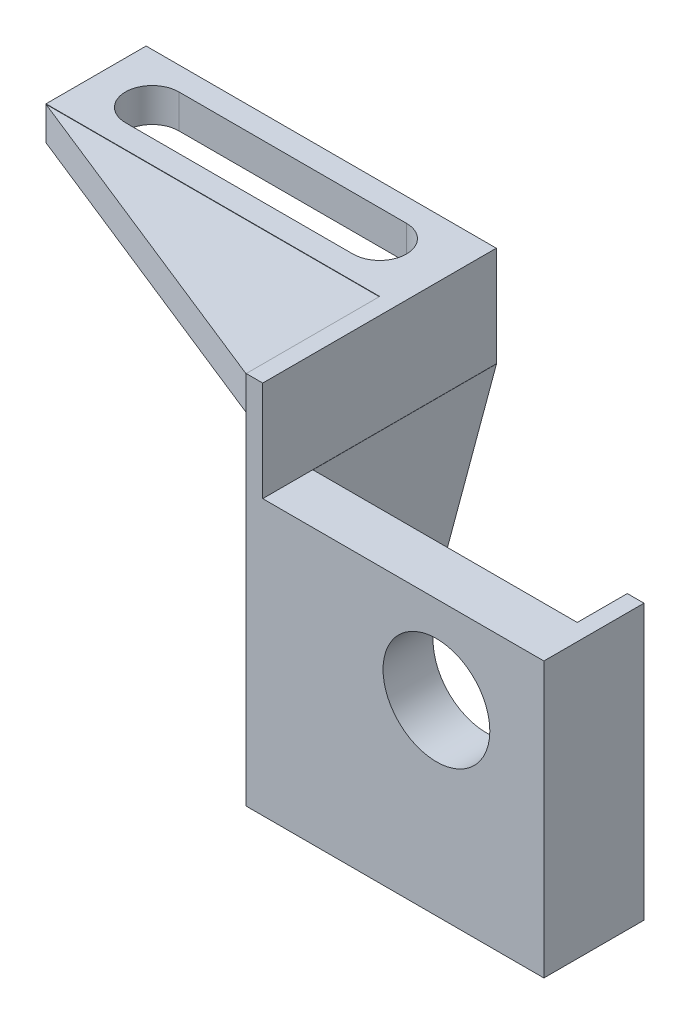
SolidWorks part; units mm, degrees
ref_plane "Front Plane" through (0, 0, 0) normal (0, 0, 1) x (1, 0, 0)
ref_plane "Top Plane" through (0, 0, 0) normal (0, 1, 0) x (1, 0, 0)
ref_plane "Right Plane" through (0, 0, 0) normal (1, 0, 0) x (0, 0, -1)
sketch "Sketch2" plane through (0, 0, 0) normal (0, 0, 1) x (1, 0, 0)
  line L0 (-6.5238, 2.0903) -> (0.8762, 2.0903) construction
  line L1 (-6.5238, 7.3453) -> (6.8762, 7.3453)
  line L2 (-6.5238, 7.3453) -> (-6.5238, -3.1647)
  line L3 (-6.5238, -3.1647) -> (6.8762, -3.1647)
  line L4 (6.8762, 7.3453) -> (6.8762, -3.1647)
  circle A0 centre (0.8762, 2.0903) radius 3.2
  dimension "D4" = 6.4
  dimension "D1" = 13.4
  dimension "D2" = 10.51
  dimension "D3" = 7.4
extrude "Boss-Extrude1" add sketch "Sketch2" along normal blind 3
sketch "Sketch4" plane through (0, 0, 3) normal (0, 0, 1) x (1, 0, 0)
  line L0 (0.8762, -1.1097) -> (0.8762, -9.1097) construction
  line L2 (-6.5238, -3.1647) -> (6.8832, -3.1647)
  line L3 (-6.5238, -3.1647) -> (-6.5238, -9.1097)
  line L4 (-6.5238, -9.1097) -> (6.8832, -9.1097)
  line L5 (6.8832, -3.1647) -> (6.8832, -9.1097)
  circle A0 centre (0.8762, 2.0903) radius 3.2 construction
  dimension "D1" = 8
extrude "Boss-Extrude3" add sketch "Sketch4" against normal blind 3
sketch "Sketch5" plane through (0, 0, 0) normal (0, 0, -1) x (-1, 0, 0)
  line L0 (-0.8762, -1.1097) -> (-0.8762, -6.0797) construction
  circle A0 centre (-0.8762, 2.0903) radius 3.2 construction
  circle A1 centre (-0.8762, -6.0797) radius 1.65
  dimension "D2" = 3.3
  dimension "D1" = 4.97
extrude "Boss-Extrude4" add sketch "Sketch5" along normal blind 3
sketch "Sketch6" plane through (-6.5238, 0, 0) normal (-1, 0, 0) x (0, 0, 1)
  line L0 (0, -7.4091) -> (0, 7.4091) construction
  line L1 (0, 7.3453) -> (3, 7.3453)
  line L2 (0, 7.3453) -> (0, -9.1097)
  line L3 (0, -9.1097) -> (3, -9.1097)
  line L4 (3, 7.3453) -> (3, -9.1097)
  line L5 (3, 7.3453) -> (0, 7.3453) construction
extrude "Boss-Extrude5" add sketch "Sketch6" along normal blind 4
sketch "Sketch7" plane through (0, 0, 0) normal (0, 0, -1) x (-1, 0, 0)
  line L0 (10.5238, -9.1097) -> (-6.8832, -9.1097) construction
  line L1 (10.5238, 7.3453) -> (9.5238, 7.3453)
  line L2 (10.5238, 7.3453) -> (10.5238, -9.1097)
  line L3 (10.5238, -9.1097) -> (9.5238, -9.1097)
  line L4 (9.5238, 7.3453) -> (9.5238, -9.1097)
  dimension "D1" = 1
extrude "Boss-Extrude6" add sketch "Sketch7" along normal blind 5
sketch "Sketch11" plane through (0, 7.3453, 0) normal (0, 1, 0) x (1, 0, 0)
  line L0 (6.8762, -3) -> (-10.5238, -3) construction
  line L1 (-10.5238, 5) -> (-9.5355, 5)
  line L2 (-10.5238, 5) -> (-10.5238, -3)
  line L3 (-10.5238, -3) -> (-9.5355, -3)
  line L4 (-9.5355, 5) -> (-9.5355, -3)
extrude "Boss-Extrude8" add sketch "Sketch11" along normal blind 6
sketch "Sketch16" plane through (0, 0, -5) normal (0, 0, -1) x (-1, 0, 0)
  line L0 (10.5238, -9.1097) -> (10.5238, 13.3453) construction
  line L1 (9.5355, 13.3453) -> (10.5238, 13.3453)
  line L2 (9.5355, 13.3453) -> (9.5355, 7.3453)
  line L3 (9.5355, 7.3453) -> (10.5238, 7.3453)
  line L4 (10.5238, 13.3453) -> (10.5238, 7.3453)
  dimension "D1" = 6
extrude "Boss-Extrude12" add sketch "Sketch16" along normal blind 6
sketch "Sketch17" plane through (-10.5238, 0, 0) normal (-1, 0, 0) x (0, 0, 1)
  line L0 (-11, 7.3453) -> (-5, -9.1097)
  line L1 (-5, -9.1097) -> (-5, 7.3453)
  line L2 (-5, 7.3453) -> (-11, 7.3453)
extrude "Boss-Extrude13" add sketch "Sketch17" against normal blind 1
sketch "Sketch20" plane through (-10.5238, 0, 0) normal (-1, 0, 0) x (0, 0, 1)
  line L1 (-11, 13.3453) -> (-5, 13.3453)
  line L2 (-11, 13.3453) -> (-11, 11.3212)
  line L3 (-11, 11.3212) -> (-5, 11.3212)
  line L4 (-5, 13.3453) -> (-5, 11.3212)
  dimension "D1" = 6
extrude "Boss-Extrude15" add sketch "Sketch20" along normal blind 20
sketch "Sketch21" plane through (0, 11.3212, 0) normal (0, -1, 0) x (1, 0, 0)
  line L0 (-30.5238, -8) -> (-6.5602, -8) construction
  line L1 (-30.5238, -11) -> (-30.5238, -5) construction
  line L2 (-20.5238, -5) -> (-20.5238, -12.6331) construction
  line L3 (-30.5238, -5) -> (-10.5238, -5) construction
  line L4 (-27.1602, -8) -> (-13.5238, -8) construction
  line L5 (-27.1602, -6.4) -> (-13.5238, -6.4)
  line L6 (-27.1602, -9.6) -> (-13.5238, -9.6)
  line L7 (-10.5238, -11) -> (-10.5238, -5) construction
  arc A0 (-27.1602, -6.4) -> (-27.1602, -9.6) centre (-27.1602, -8) ccw
  arc A1 (-13.5238, -9.6) -> (-13.5238, -6.4) centre (-13.5238, -8) ccw
  point P10 (-20.342, -8)
  dimension "D1" = 3.2
  dimension "D2" = 3
extrude "Cut-Extrude3" cut sketch "Sketch21" against normal through all
sketch "Sketch22" plane through (6.8762, 0, 0) normal (1, 0, 0) x (0, 0, -1)
  line L1 (-3, 7.3453) -> (0, 7.3453)
  line L2 (-3, 7.3453) -> (-3, -9.1097)
  line L3 (-3, -9.1097) -> (0, -9.1097)
  line L4 (0, 7.3453) -> (0, -9.1097)
extrude "Boss-Extrude16" add sketch "Sketch22" along normal blind 0.44
sketch "Sketch23" plane through (0, 0, 0) normal (0, 0, -1) x (-1, 0, 0)
  line L0 (9.5238, -9.1097) -> (-7.3162, -9.1097) construction
  line L1 (-7.3162, 7.3453) -> (-6.3162, 7.3453)
  line L2 (-7.3162, 7.3453) -> (-7.3162, -9.1097)
  line L3 (-7.3162, -9.1097) -> (-6.3162, -9.1097)
  line L4 (-6.3162, 7.3453) -> (-6.3162, -9.1097)
  dimension "D1" = 1
extrude "Boss-Extrude17" add sketch "Sketch23" along normal blind 3
sketch "Sketch24" plane through (0, 11.3212, 0) normal (0, -1, 0) x (1, 0, 0)
  line L0 (-30.5238, -5) -> (-10.5238, -5)
  line L1 (-10.5238, -5) -> (-10.5238, 3)
  line L2 (-10.5238, 3) -> (-30.5238, -5)
  dimension "D1" = 8
extrude "Boss-Extrude18" add sketch "Sketch24" against normal blind 2
